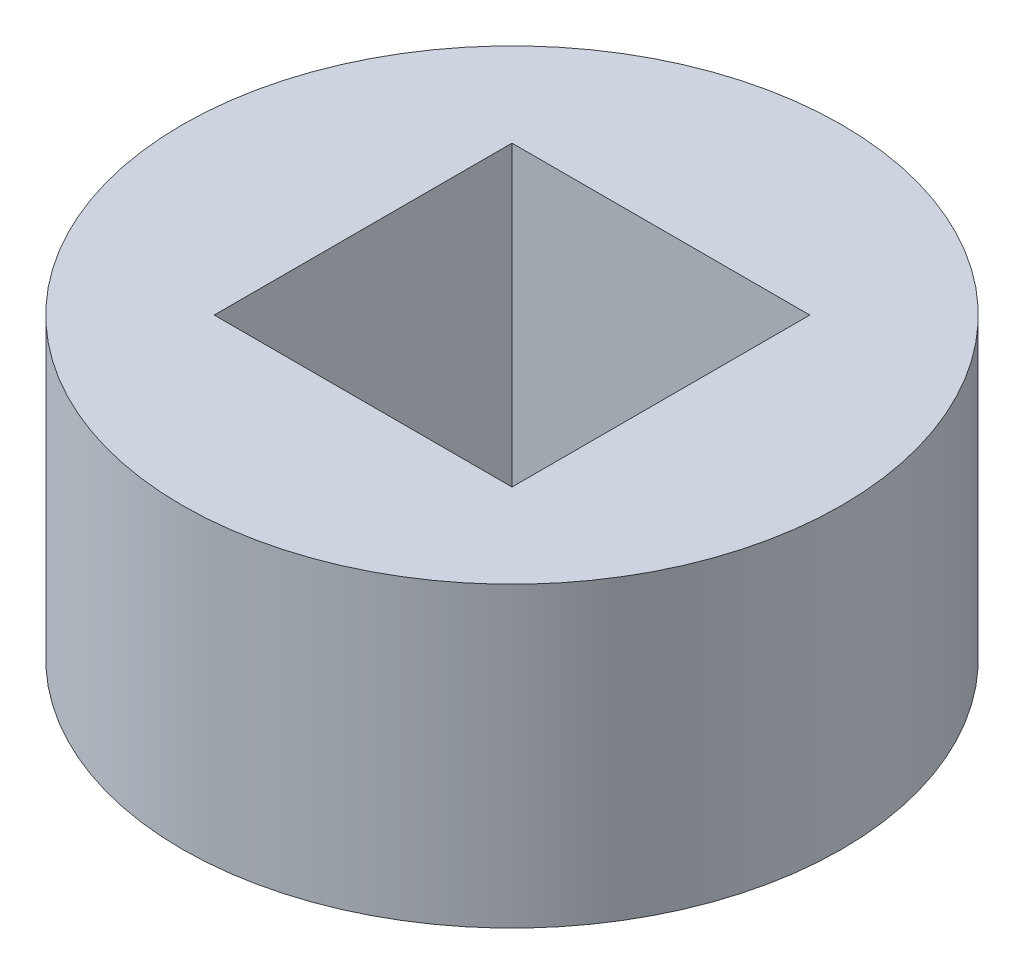
SolidWorks part; units mm, degrees
ref_plane "Front Plane" through (0, 0, 0) normal (0, 0, 1) x (1, 0, 0)
ref_plane "Top Plane" through (0, 0, 0) normal (0, 1, 0) x (1, 0, 0)
ref_plane "Right Plane" through (0, 0, 0) normal (1, 0, 0) x (0, 0, -1)
sketch "Elevator Axle Bearing" plane through (0, 0, 0) normal (0, 1, 0) x (1, 0, 0)
  line L1 (-3.175, 3.175) -> (3.175, 3.175)
  line L2 (-3.175, 3.175) -> (-3.175, -3.175)
  line L3 (-3.175, -3.175) -> (3.175, -3.175)
  line L4 (3.175, 3.175) -> (3.175, -3.175)
  line L5 (-3.175, 3.175) -> (3.175, -3.175) construction
  line L6 (-3.175, -3.175) -> (3.175, 3.175) construction
  circle A0 centre (0, 0) radius 7.0301
  dimension "D1" = 14.0603
  dimension "D2" = 6.35
  dimension "D3" = 6.35
extrude "Boss-Extrude1" add sketch "Elevator Axle Bearing" along normal blind 6.35
equation "\"Ball Diameter\"= 1.75in"
equation "\"Sheet Thickness\"= 0.25in"
equation "\"Screw Diameter\"= .17in"
equation "\"Robot Diameter\"= 14in"
equation "\"Castor Screw Diameter\"= 0.22in"
equation "\"Wheel Diameter\" = 4in"
equation "\"Nut Diameter\" = 8.4mm"
equation "\"Nut Height\" = 2.9mm"
equation "\"Screw Height\" = 0.55in"
equation "\"Pulley Diameter\" = 1in"
equation "\"Reactor Height\" = 14in"
equation "\"Elevator Height\" = 11.5in"
equation "\"Elevator Width\" = \"Ball Diameter\" + 0.25in"
equation "\"Elevator Bearing Diameter\" = sqr(2*(\"Sheet Thickness\"^2)) + 0.2in"
equation "\"Elevator Axle Length\" = \"Elevator Width\" + 6*\"Sheet Thickness\""
equation "\"D1@Elevator Axle Bearing\"=\"Elevator Bearing Diameter\""
equation "\"D2@Elevator Axle Bearing\"=\"Sheet Thickness\""
equation "\"D3@Elevator Axle Bearing\"=\"Sheet Thickness\""
equation "\"D1@Boss-Extrude1\"=\"Sheet Thickness\""
